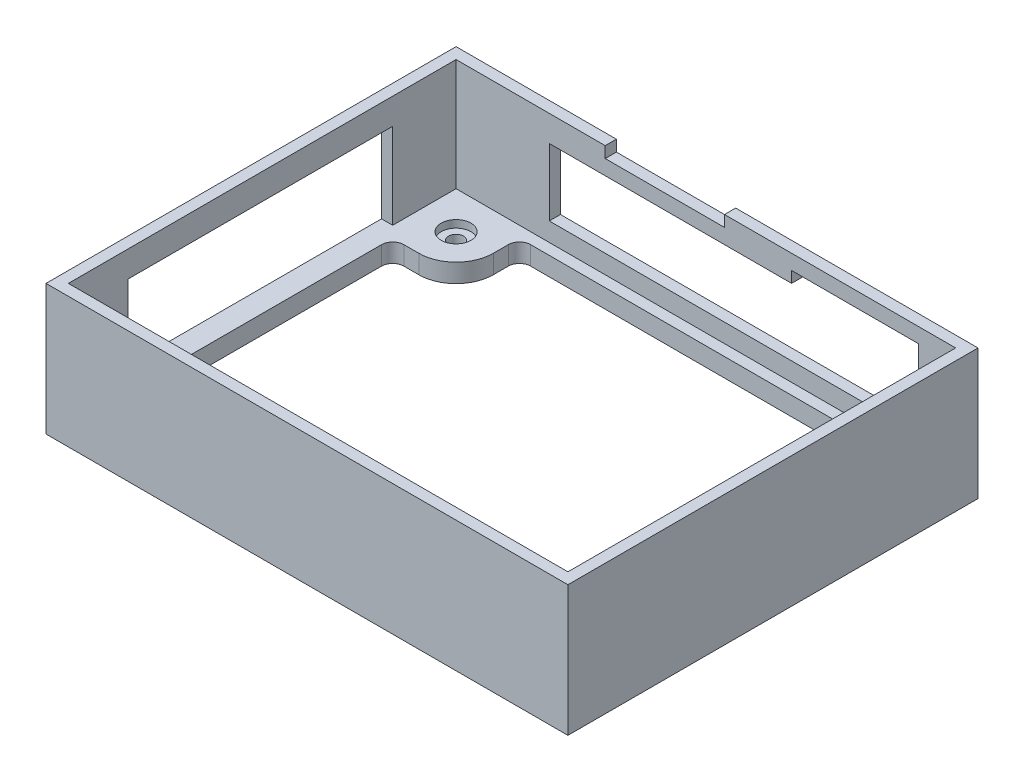
SolidWorks part; units mm, degrees
ref_plane "Front Plane" through (0, 0, 0) normal (0, 0, 1) x (1, 0, 0)
ref_plane "Top Plane" through (0, 0, 0) normal (0, 1, 0) x (1, 0, 0)
ref_plane "Right Plane" through (0, 0, 0) normal (1, 0, 0) x (0, 0, -1)
sketch "Sketch1" plane through (0, 0, 0) normal (0, 1, 0) x (1, 0, 0)
  line L1 (0, 0) -> (140, 0)
  line L2 (0, 0) -> (0, -110)
  line L3 (0, -110) -> (140, -110)
  line L4 (140, 0) -> (140, -110)
  dimension "D1" = 140
  dimension "D2" = 110
extrude "Boss-Extrude1" add sketch "Sketch1" along normal blind 5
sketch "Sketch3" plane through (0, 5, 0) normal (0, 1, 0) x (1, 0, 0)
  line L4 (140, -110) -> (140, 0) construction
  line L5 (0, -110) -> (140, -110) construction
  line L6 (140, 0) -> (0, 0) construction
  line L7 (0, 0) -> (0, -110) construction
  line L8 (3, -3) -> (3, -107)
  line L9 (3, -107) -> (137, -107)
  line L10 (137, -107) -> (137, -3)
  line L11 (137, -3) -> (3, -3)
  line L12 (3, -3) -> (3, -107)
  line L13 (3, -107) -> (137, -107)
  line L14 (137, -107) -> (137, -3)
  line L15 (137, -3) -> (3, -3)
  line L16 (140, -110) -> (140, 0)
  line L17 (0, -110) -> (140, -110)
  line L18 (140, 0) -> (0, 0)
  line L19 (0, 0) -> (0, -110)
  dimension "D1" = 3
extrude "Boss-Extrude2" add sketch "Sketch3" along normal blind 30
sketch "Sketch4" plane through (0, 5, 0) normal (0, 1, 0) x (1, 0, 0)
  line L0 (23, -6) -> (23, -23)
  line L1 (23, -23) -> (6, -23)
  line L2 (6, -23) -> (6, -87)
  line L3 (6, -87) -> (23, -87)
  line L4 (23, -87) -> (23, -104)
  line L5 (23, -104) -> (117, -104)
  line L6 (117, -104) -> (117, -87)
  line L7 (117, -87) -> (134, -87)
  line L8 (134, -87) -> (134, -23)
  line L9 (134, -23) -> (117, -23)
  line L10 (117, -23) -> (117, -6)
  line L11 (117, -6) -> (23, -6)
  line L12 (137, -3) -> (3, -3) construction
  line L13 (3, -107) -> (137, -107) construction
  line L14 (137, -107) -> (137, -3) construction
  line L15 (3, -3) -> (3, -107) construction
  dimension "D1" = 3
  dimension "D2" = 3
  dimension "D3" = 3
  dimension "D4" = 3
  dimension "D5" = 17
  dimension "D6" = 17
  dimension "D7" = 17
  dimension "D8" = 17
  dimension "D9" = 17
  dimension "D10" = 17
  dimension "D11" = 17
  dimension "D12" = 17
extrude "Cut-Extrude3" cut sketch "Sketch4" against normal up to surface (5 mm away) up to face at (70, 0, 55)
fillet "Fillet1" radius 3 8 edges at (117, 2.5, 104) (134, 2.5, 87) (117, 2.5, 6) (134, 2.5, 23) (23, 2.5, 104) (6, 2.5, 87) (6, 2.5, 23) (23, 2.5, 6)
sketch "Sketch5" plane through (0, 5, 0) normal (0, 1, 0) x (1, 0, 0)
  line L0 (13, -3) -> (13, -23) construction
  line L1 (137, -3) -> (3, -3) construction
  line L2 (3, -3) -> (3, -107) construction
  line L9 (13, -90) -> (13, -104) construction
  line L10 (3, -107) -> (137, -107) construction
  circle A0 centre (13, -13) radius 4
  circle A1 centre (13, -97) radius 4
  dimension "D1" = 8
  dimension "D4" = 8
  dimension "D2" = 10
  dimension "D3" = 10
  dimension "D5" = 10
  dimension "D6" = 10
extrude "Cut-Extrude4" cut sketch "Sketch5" against normal blind 2
sketch "Sketch6" plane through (0, 5, 0) normal (0, 1, 0) x (1, 0, 0)
  circle A0 centre (13, -13) radius 2
  circle A1 centre (13, -97) radius 2
  dimension "D1" = 4
  dimension "D2" = 4
extrude "Cut-Extrude5" cut sketch "Sketch6" against normal up to surface (5 mm away) up to face at (70, 0, 55)
ref_plane "Plane1" through (70, 0, 0) normal (1, 0, 0) x (0, 0, -1)
mirror "Mirror1" about plane through (70, 0, 0) normal (1, 0, 0) of "Cut-Extrude5", "Cut-Extrude4"
fillet "Fillet2" radius 10 4 edges at (117, 2.5, 23) (23, 2.5, 23) (23, 2.5, 87) (117, 2.5, 87)
sketch "Sketch8" plane through (0, 0, 0) normal (0, 0, -1) x (-1, 0, 0)
  line L0 (-140, 0) -> (0, 0) construction
  line L2 (-127, 31) -> (-127, 10)
  line L3 (-127, 10) -> (-28, 10)
  line L5 (-140, 35) -> (-140, 0) construction
  line L8 (-127, 31) -> (-93, 31)
  line L14 (-93, 31) -> (-93, 28)
  line L15 (-93, 28) -> (-28, 28)
  line L16 (-28, 10) -> (-28, 28)
  line L17 (0, 35) -> (0, 0) construction
  point P8 (-140, 17.5)
  dimension "D1" = 10
  dimension "D2" = 13
  dimension "D3" = 28
  dimension "D4" = 3
  dimension "D5" = 34
  dimension "D6" = 21
extrude "Cut-Extrude6" cut sketch "Sketch8" against normal up to surface (3 mm away) up to face at (70, 20, 3)
sketch "Sketch9" plane through (0, 0, 0) normal (0, 0, -1) x (-1, 0, 0)
  line L0 (-140, 35) -> (0, 35) construction
  line L1 (-75, 35) -> (-43, 35)
  line L2 (-75, 35) -> (-75, 32)
  line L3 (-75, 32) -> (-43, 32)
  line L4 (-43, 35) -> (-43, 32)
  line L5 (-127, 31) -> (-127, 10) construction
  dimension "D1" = 52
  dimension "D2" = 32
  dimension "D3" = 3
extrude "Cut-Extrude7" cut sketch "Sketch9" against normal up to surface (3 mm away) up to face at (82.6667, 23, 3)
sketch "Sketch10" plane through (0, 0, 0) normal (-1, 0, 0) x (0, 0, 1)
  line L0 (0, 35) -> (0, 0) construction
  line L1 (20, 28) -> (91, 28)
  line L2 (20, 28) -> (20, 5)
  line L3 (20, 5) -> (91, 5)
  line L4 (91, 28) -> (91, 5)
  line L5 (110, 35) -> (110, 0) construction
  line L6 (0, 0) -> (110, 0) construction
  dimension "D1" = 20
  dimension "D2" = 19
  dimension "D3" = 5
  dimension "D4" = 23
extrude "Cut-Extrude8" cut sketch "Sketch10" against normal up to surface (3 mm away) up to face at (3, 20, 55)
